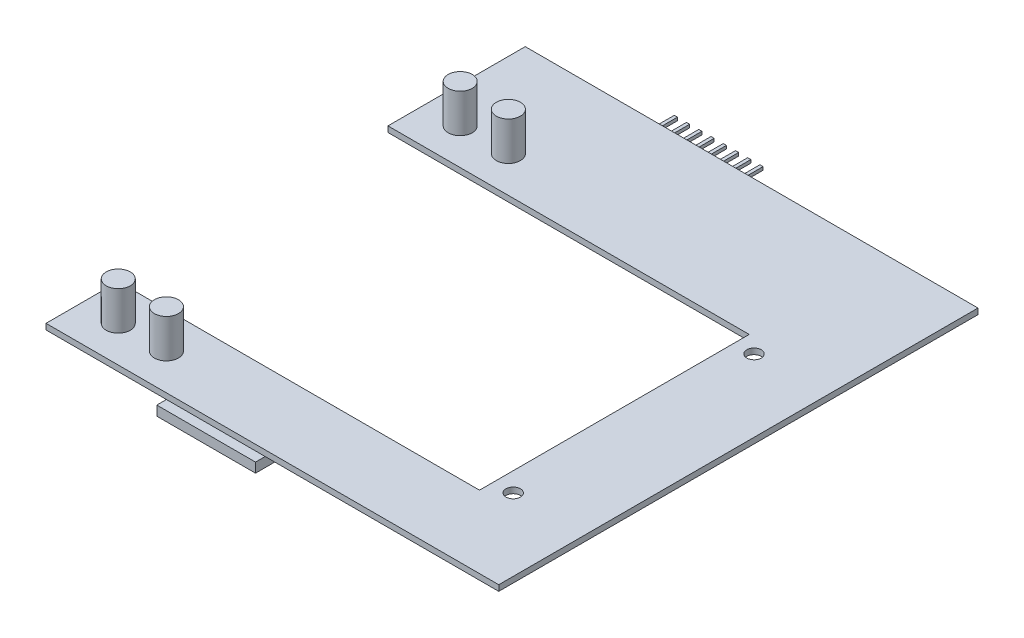
SolidWorks part; units mm, degrees
ref_plane "Płaszczyzna przednia" through (0, 0, 0) normal (0, 0, 1) x (1, 0, 0)
ref_plane "Płaszczyzna górna" through (0, 0, 0) normal (0, 1, 0) x (1, 0, 0)
ref_plane "Płaszczyzna prawa" through (0, 0, 0) normal (1, 0, 0) x (0, 0, -1)
sketch "Szkic2" plane through (0, 566.3703, 0) normal (0, 1, 0) x (1, 0, 0)
  line L0 (-513.8264, 398.4729) -> (-513.8264, 383.4729)
  line L1 (-513.8264, 482.9729) -> (-419.8264, 482.9729)
  line L2 (-513.8264, 383.4729) -> (-419.8264, 383.4729)
  line L3 (-419.8264, 482.9729) -> (-419.8264, 383.4729)
  line L6 (-513.8264, 482.9729) -> (-513.8264, 454.4729)
  line L7 (-513.8264, 454.4729) -> (-438.8264, 454.4729)
  line L9 (-438.8264, 454.4729) -> (-438.8264, 398.4729)
  line L10 (-513.8264, 398.4729) -> (-438.8264, 398.4729)
  line L11 (-438.8264, 451.4729) -> (-438.8264, 401.4729) construction
  line L13 (-438.8264, 401.4729) -> (-518.8264, 401.4729) construction
  line L14 (-418.8264, 1218.7103) -> (-418.8264, 318.7103) construction
  line L15 (-518.8264, 451.4729) -> (-438.8264, 451.4729) construction
  point P3 (-478.8264, 401.4729)
  dimension "D1" = 15
  dimension "D2" = 3
  dimension "D3" = 94
  dimension "D4" = 1
  dimension "D5" = 99.5
  dimension "D6" = 3
  dimension "D7" = 28.5
  dimension "D8" = 19
extrude "Dodanie-wyciągnięcie1" add sketch "Szkic2" along normal blind 1.2
sketch "Szkic3" plane through (0, 567.5703, 0) normal (0, 1, 0) x (1, 0, 0)
  line L0 (-513.8264, 482.9729) -> (-513.8264, 454.4729) construction
  line L1 (-513.8264, 454.4729) -> (-438.8264, 454.4729) construction
  line L2 (-438.8264, 398.4729) -> (-513.8264, 398.4729) construction
  line L3 (-513.8264, 398.4729) -> (-513.8264, 383.4729) construction
  circle A0 centre (-506.3264, 461.9729) radius 2.5
  circle A1 centre (-496.3264, 461.9729) radius 2.5
  circle A2 centre (-496.3264, 390.9729) radius 2.5
  circle A3 centre (-506.3264, 390.9729) radius 2.5
  dimension "D1" = 7.5
  dimension "D2" = 7.5
  dimension "D3" = 10
  dimension "D4" = 7.5
  dimension "D5" = 7.5
  dimension "D6" = 7.5
  dimension "D7" = 10
  dimension "D8" = 7.5
extrude "Dodanie-wyciągnięcie2" add sketch "Szkic3" along normal blind 8
sketch "Szkic4" plane through (0, 567.5703, 0) normal (0, 1, 0) x (1, 0, 0)
  line L0 (-513.8264, 383.4729) -> (-419.8264, 383.4729) construction
  line L1 (-419.8264, 383.4729) -> (-419.8264, 482.9729) construction
  circle A0 centre (-434.8264, 401.4729) radius 1.5
  circle A1 centre (-434.8264, 451.4729) radius 1.5
  dimension "D1" = 3
  dimension "D2" = 3
  dimension "D3" = 18
  dimension "D4" = 50
  dimension "D5" = 15
  dimension "D6" = 15
extrude "Wytnij-wyciągnięcie1" cut sketch "Szkic4" against normal through all
sketch "Szkic5" plane through (0, 566.3703, 0) normal (0, -1, 0) x (1, 0, 0)
  line L0 (-508.8264, -477.9729) -> (-503.8264, -477.9729)
  line L1 (-508.8264, -477.9729) -> (-508.8264, -472.9729)
  line L2 (-503.8264, -477.9729) -> (-503.8264, -472.9729)
  line L3 (-508.8264, -472.9729) -> (-503.8264, -472.9729)
  line L4 (-498.8264, -477.9729) -> (-493.8264, -477.9729)
  line L5 (-498.8264, -477.9729) -> (-498.8264, -472.9729)
  line L6 (-493.8264, -477.9729) -> (-493.8264, -472.9729)
  line L7 (-498.8264, -472.9729) -> (-493.8264, -472.9729)
  line L8 (-419.8264, -482.9729) -> (-513.8264, -482.9729) construction
  line L9 (-513.8264, -482.9729) -> (-513.8264, -454.4729) construction
  dimension "D1" = 5
  dimension "D2" = 5
  dimension "D3" = 5
  dimension "D4" = 5
  dimension "D5" = 5
  dimension "D6" = 5
  dimension "D7" = 5
extrude "Dodanie-wyciągnięcie3" add sketch "Szkic5" along normal blind 1
sketch "Szkic6" plane through (0, 566.3703, 0) normal (0, -1, 0) x (-1, 0, 0)
  line L0 (483.8264, 467.9729) -> (483.8264, 459.9729)
  line L1 (483.8264, 467.9729) -> (475.8264, 467.9729)
  line L2 (483.8264, 459.9729) -> (475.8264, 459.9729)
  line L3 (475.8264, 467.9729) -> (475.8264, 459.9729)
  line L4 (419.8264, 482.9729) -> (513.8264, 482.9729) construction
  line L5 (513.8264, 482.9729) -> (513.8264, 454.4729) construction
  dimension "D1" = 8
  dimension "D2" = 8
  dimension "D3" = 15
  dimension "D4" = 30
extrude "Dodanie-wyciągnięcie4" add sketch "Szkic6" along normal blind 3
sketch "Szkic7" plane through (0, 563.3703, 0) normal (0, -1, 0) x (1, 0, 0)
  line L0 (-483.8264, -459.9729) -> (-483.8264, -467.9729) construction
  line L1 (-475.8264, -459.9729) -> (-483.8264, -459.9729) construction
  circle A0 centre (-479.8264, -463.9729) radius 2.5
  dimension "D1" = 5
  dimension "D2" = 4
  dimension "D3" = 4
extrude "Dodanie-wyciągnięcie5" add sketch "Szkic7" along normal blind 3
sketch "Szkic8" plane through (0, 566.3703, 0) normal (0, -1, 0) x (-1, 0, 0)
  line L0 (488.8264, 477.9729) -> (468.3264, 477.9729)
  line L1 (488.8264, 477.9729) -> (488.8264, 481.9729)
  line L2 (468.3264, 477.9729) -> (468.3264, 481.9729)
  line L3 (488.8264, 481.9729) -> (468.3264, 481.9729)
  line L4 (419.8264, 482.9729) -> (513.8264, 482.9729) construction
  line L5 (468.3264, 391.4729) -> (488.8264, 391.4729)
  line L6 (468.3264, 391.4729) -> (468.3264, 381.4729)
  line L7 (488.8264, 391.4729) -> (488.8264, 381.4729)
  line L8 (468.3264, 381.4729) -> (488.8264, 381.4729)
  line L9 (513.8264, 482.9729) -> (513.8264, 454.4729) construction
  line L10 (513.8264, 383.4729) -> (419.8264, 383.4729) construction
  line L11 (513.8264, 398.4729) -> (513.8264, 383.4729) construction
  dimension "D1" = 20.5
  dimension "D2" = 4
  dimension "D3" = 5
  dimension "D4" = 25
  dimension "D5" = 10
  dimension "D6" = 20.5
  dimension "D7" = 8
  dimension "D8" = 25
extrude "Dodanie-wyciągnięcie6" add sketch "Szkic8" along normal blind 2
sketch "Szkic9" plane through (0, 0, -481.9729) normal (0, 0, -1) x (-1, 0, 0)
  line L0 (487.8864, 565.6903) -> (487.2264, 565.6903)
  line L1 (487.8864, 565.6903) -> (487.8864, 565.0303)
  line L2 (487.2264, 565.6903) -> (487.2264, 565.0303)
  line L3 (487.8864, 565.0303) -> (487.2264, 565.0303)
  line L4 (488.8264, 564.3703) -> (468.3264, 564.3703) construction
  line L5 (488.8264, 564.3703) -> (488.8264, 566.3703) construction
  dimension "D1" = 0.66
  dimension "D2" = 0.66
  dimension "D3" = 0.66
  dimension "D4" = 0.94
extrude "Dodanie-wyciągnięcie7" add sketch "Szkic9" along normal blind 6
pattern_linear "Szyk liniowy1" count 8 spacing 2.54 along (1, 0, 0) of "Dodanie-wyciągnięcie7"
sketch "Szkic10" plane through (0, 566.3703, 0) normal (0, -1, 0) x (-1, 0, 0)
  line L0 (463.3264, 474.9729) -> (453.3264, 474.9729)
  line L1 (463.3264, 474.9729) -> (463.3264, 462.9729)
  line L2 (453.3264, 474.9729) -> (453.3264, 462.9729)
  line L3 (463.3264, 462.9729) -> (453.3264, 462.9729)
  line L4 (468.3264, 481.9729) -> (468.3264, 477.9729) construction
  line L5 (419.8264, 482.9729) -> (513.8264, 482.9729) construction
  line L6 (449.8264, 474.9729) -> (449.8264, 462.9729)
  line L7 (449.8264, 474.9729) -> (444.8264, 474.9729)
  line L8 (449.8264, 462.9729) -> (444.8264, 462.9729)
  line L9 (444.8264, 474.9729) -> (444.8264, 462.9729)
  line L10 (438.8264, 454.4729) -> (438.8264, 398.4729) construction
  dimension "D1" = 12
  dimension "D2" = 10
  dimension "D3" = 5
  dimension "D4" = 8
  dimension "D5" = 5
  dimension "D6" = 12
  dimension "D7" = 8
  dimension "D8" = 6
extrude "Dodanie-wyciągnięcie8" add sketch "Szkic10" along normal blind 2
